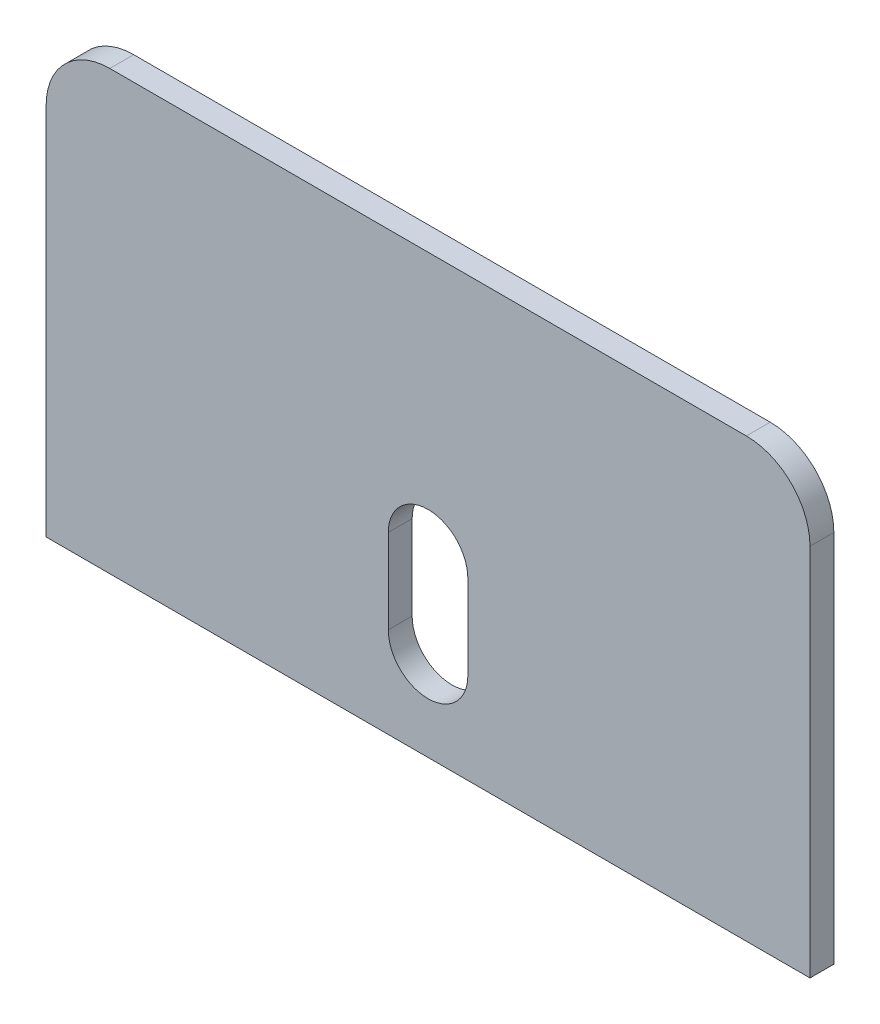
SolidWorks part; units mm, degrees
other "Camera1"
material "3.0517 (EN-AW 3003)"
ref_plane "Front Plane" through (0, 0, 0) normal (0, 0, 1) x (1, 0, 0)
ref_plane "Top Plane" through (0, 0, 0) normal (0, 1, 0) x (1, 0, 0)
ref_plane "Right Plane" through (0, 0, 0) normal (1, 0, 0) x (0, 0, -1)
sketch "Sketch1" plane through (0, 0, 0) normal (0, 0, 1) x (1, 0, 0)
  line L0 (0, -16.1) -> (0, -5.5) construction
  line L1 (48, -27.5) -> (-48, -27.5)
  line L2 (48, -27.5) -> (48, 27.5)
  line L3 (48, 27.5) -> (-48, 27.5)
  line L4 (-48, -27.5) -> (-48, 27.5)
  line L5 (48, -27.5) -> (-48, 27.5) construction
  line L6 (48, 27.5) -> (-48, -27.5) construction
  line L7 (-5, -16.1) -> (-5, -5.5)
  line L8 (5, -16.1) -> (5, -5.5)
  arc A0 (-5, -16.1) -> (5, -16.1) centre (0, -16.1) ccw
  arc A1 (5, -5.5) -> (-5, -5.5) centre (0, -5.5) ccw
  point P0 (0, 0)
  point P8 (0, -10.8)
  dimension "D4" = 5
  dimension "D1" = 55
  dimension "D2" = 96
  dimension "D3" = 10.6
  dimension "D5" = 11.4
extrude "Boss-Extrude1" add sketch "Sketch1" along normal mid plane 3
sketch "Sketch2" plane through (0, 0, -1.5) normal (0, 0, -1) x (-1, 0, 0)
  line L0 (-48, -17.5) -> (-54, -17.5)
  line L1 (-48, -27.5) -> (-48, 27.5) construction
  line L2 (-54, -17.5) -> (-54, -14.5)
  line L3 (-54, -14.5) -> (-48, -14.5)
  line L4 (48, -27.5) -> (-48, -27.5) construction
  line L5 (-38, -27.5) -> (-38, -33.5)
  line L6 (-38, -33.5) -> (-35, -33.5)
  line L7 (-35, -33.5) -> (-35, -27.5)
  line L8 (0, 27.5) -> (0, -27.5) construction
  line L9 (-48, 27.5) -> (48, 27.5) construction
  line L10 (48, 0) -> (-48, 0) construction
  line L11 (48, 27.5) -> (48, -27.5) construction
  line L12 (35, -33.5) -> (35, -27.5)
  line L13 (38, -33.5) -> (35, -33.5)
  line L14 (38, -27.5) -> (38, -33.5)
  line L15 (54, -14.5) -> (48, -14.5)
  line L16 (54, -17.5) -> (54, -14.5)
  line L17 (48, -17.5) -> (54, -17.5)
  line L18 (48, 17.5) -> (54, 17.5)
  line L19 (54, 17.5) -> (54, 14.5)
  line L20 (54, 14.5) -> (48, 14.5)
  line L21 (38, 27.5) -> (38, 33.5)
  line L22 (38, 33.5) -> (35, 33.5)
  line L23 (35, 33.5) -> (35, 27.5)
  line L24 (-35, 33.5) -> (-35, 27.5)
  line L25 (-38, 33.5) -> (-35, 33.5)
  line L26 (-38, 27.5) -> (-38, 33.5)
  line L27 (-54, 14.5) -> (-48, 14.5)
  line L28 (-54, 17.5) -> (-54, 14.5)
  line L29 (-48, 17.5) -> (-54, 17.5)
  dimension "D1" = 6
  dimension "D2" = 3
  dimension "D3" = 3
  dimension "D4" = 6
  dimension "D5" = 10
  dimension "D6" = 10
fillet "Fillet1" radius 8 2 edges at (48, 27.5, 0) (-48, 27.5, 0)
